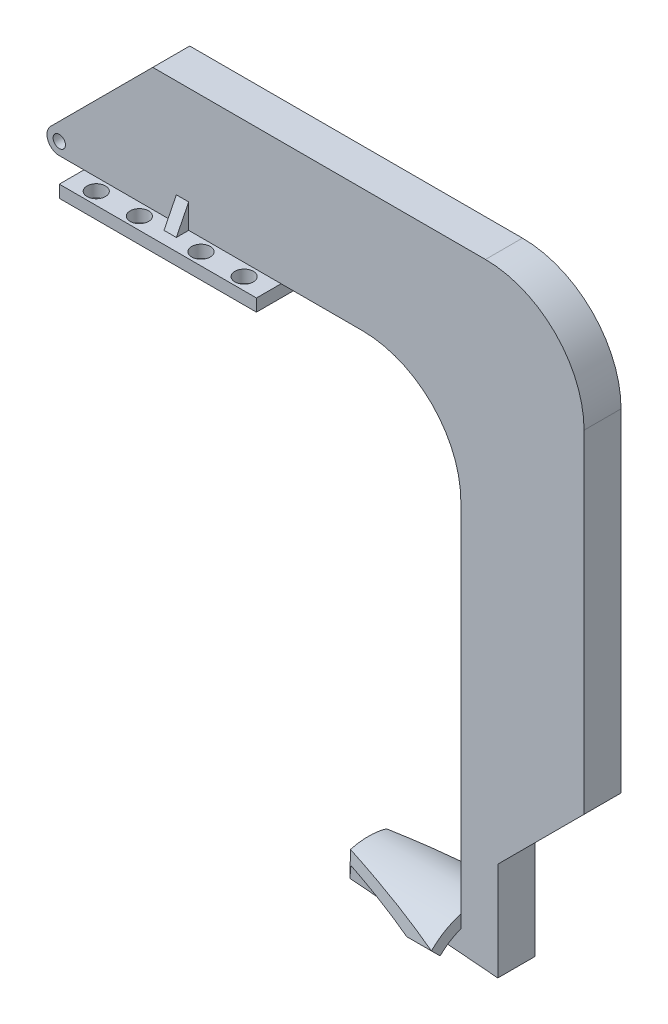
SolidWorks part; units mm, degrees
material "Stainless Steel (ferritic)"
ref_plane "Front Plane" through (0, 0, 0) normal (0, 0, 1) x (1, 0, 0)
ref_plane "Top Plane" through (0, 0, 0) normal (0, 1, 0) x (1, 0, 0)
ref_plane "Right Plane" through (0, 0, 0) normal (1, 0, 0) x (0, 0, -1)
sketch "Sketch1" plane through (0, 0, 0) normal (0, 0, 1) x (1, 0, 0)
  line L0 (-7.0711, 7.0711) -> (75.8579, 90)
  line L1 (75.8579, 90) -> (345.8579, 90)
  line L2 (425.8579, 10) -> (425.8579, -260)
  line L3 (425.8579, -260) -> (355.8579, -330)
  line L4 (355.8579, -330) -> (355.8579, -410)
  line L5 (355.8579, -410) -> (235.8579, -400)
  line L6 (235.8579, -400) -> (235.8579, -380)
  line L7 (235.8579, -380) -> (325.8579, -380)
  line L8 (325.8579, -380) -> (325.8579, -90)
  line L9 (245.8579, -10) -> (0, -10)
  arc A0 (325.8579, -90) -> (245.8579, -10) centre (245.8579, -90) ccw
  arc A1 (345.8579, 90) -> (425.8579, 10) centre (345.8579, 10) cw
  arc A2 (-7.0711, 7.0711) -> (0, -10) centre (0, 0) ccw
  circle A3 centre (0, 0) radius 5
  point P24 (325.8579, -10)
  point P27 (425.8579, 90)
  dimension "D11" = 80
  dimension "D12" = 20
  dimension "D13" = 10
  dimension "D1" = 500
  dimension "D2" = 100
  dimension "D3" = 100
  dimension "D4" = 30
  dimension "D5" = 45
  dimension "D6" = 350
  dimension "D7" = 370
  dimension "D8" = 10
  dimension "D9" = 350
  dimension "D10" = 120
extrude "Boss-Extrude1" add sketch "Sketch1" along normal blind 30
sketch "Sketch2" plane through (0, -10, 0) normal (0, -1, 0) x (1, 0, 0)
  line L0 (0, 30) -> (0, 0) construction
  line L1 (20, -20) -> (180, -20)
  line L2 (20, -20) -> (20, 50)
  line L3 (20, 50) -> (180, 50)
  line L4 (180, -20) -> (180, 50)
  line L5 (0, 30) -> (0, 0)
  point P6 (0, 15)
  point P7 (20, 15)
  line M3 (0, 0) -> (245.8579, 0)
  line M5 (245.8579, 30) -> (0, 30)
  dimension "D1" = 160
  dimension "D2" = 70
  dimension "D3" = 20
extrude "Boss-Extrude2" add sketch "Sketch2" along normal blind 10 contours L4 L3 L2 M5 | L4 L2 M3 M5 | L1 L4 L2 M3
ref_plane "Plane2" through (100, 0, 0) normal (-1, 0, 0) x (0, 0, 1)
sketch "Sketch5" plane through (100, 0, 0) normal (-1, 0, 0) x (0, 0, 1)
  line L0 (30, 10) -> (40, -10)
  line L1 (30, -10) -> (30, 7.0711) construction
  line L2 (30, -10) -> (50, -10) construction
  line L3 (30, 90) -> (30, 7.0711) construction
  point P6 (30, 10.9704)
  point P9 (0, 0)
  point P10 (42.7835, -10)
  dimension "D1" = 10
  dimension "D2" = 20
rib "Rib1" sketch "Sketch5" sketch "Sketch5" thickness 10 extrusion direction parallel to sketch draft on no parameters "D1"=10
sketch "Sketch7" plane through (100, 0, 0) normal (-1, 0, 0) x (0, 0, 1)
  line L0 (0, 10) -> (-10, -10)
  line L1 (0, 90) -> (0, 7.0711) construction
  line L2 (-20, -10) -> (0, -10) construction
  dimension "D1" = 20
  dimension "D2" = 10
rib "Rib17" sketch "Sketch7" sketch "Sketch7" thickness 10 extrusion direction parallel to sketch draft on no parameters "D1"=10
sketch "Sketch8" plane through (0, -20, 0) normal (0, -1, 0) x (1, 0, 0)
  line L0 (20, 0) -> (95, 0) construction
  line L1 (105, 0) -> (180, 0) construction
  line L2 (105, 30) -> (180, 30) construction
  line L3 (20, 30) -> (95, 30) construction
  line L4 (20, 0) -> (95, 0)
  line L5 (105, 0) -> (180, 0)
  line L6 (105, 30) -> (180, 30)
  line L7 (20, 30) -> (95, 30)
  line L8 (180, 0) -> (180, 30) construction
  line L9 (180, 0) -> (180, 30)
  line L10 (40, 40) -> (40, -10) construction
  line L11 (20, 50) -> (20, 30) construction
  line L12 (40, 40) -> (75, 40) construction
  line L13 (125, 40) -> (160, 40) construction
  circle A0 centre (40, 40) radius 7.5
  circle A1 centre (75, 40) radius 7.5
  circle A2 centre (125, 40) radius 7.5
  circle A3 centre (160, 40) radius 7.5
  circle A4 centre (40, -10) radius 7.5
  circle A5 centre (75, -10) radius 7.5
  circle A6 centre (125, -10) radius 7.5
  circle A7 centre (160, -10) radius 7.5
  point P24 (180, 15)
  point P25 (40, 15)
  point P26 (57.5, 40)
  point P27 (20, 40)
  point P28 (57.5, 30)
  point P29 (142.5, 40)
  point P30 (142.5, 30)
  dimension "D1" = 15
  dimension "D2" = 35
  dimension "D3" = 35
extrude "Cut-Extrude1" cut sketch "Sketch8" against normal blind 10 contours A0 | A1 | A4 | A5 | A6 | A7 | A3 | A2
sketch "Sketch9" plane through (325.8579, 0, 0) normal (-1, 0, 0) x (0, 0, 1)
  line L0 (-23.8909, -394.0242) -> (-16.8198, -401.0952)
  line L1 (46.8198, -401.0952) -> (53.8909, -394.0242)
  line L2 (15, -432.915) -> (15, -424.2734) construction
  line L3 (53.8909, -394.0242) -> (15, -432.915) construction
  line L4 (15, -432.915) -> (-23.8909, -394.0242) construction
  arc A0 (53.8909, -394.0242) -> (-23.8909, -394.0242) centre (15, -432.915) ccw
  arc A1 (46.8198, -401.0952) -> (-16.8198, -401.0952) centre (15, -432.915) ccw
  circle A2 centre (15, -432.915) radius 55 construction
  circle A3 centre (15, -432.915) radius 45 construction
  dimension "D1" = 110
  dimension "D3" = 90
  dimension "D2" = 10
extrude "Boss-Extrude3" add sketch "Sketch9" along normal up to surface (90 mm away) up to face at (235.8579, -390, 15)
sketch "Sketch10" plane through (-31.4768, -377.7221, 0) normal (-0.083, -0.9965, 0) x (0.9965, -0.083, 0)
  line L4 (357.4542, 53.8909) -> (268.2613, 30)
  line L5 (357.4542, -23.8909) -> (268.2613, 0)
  line L9 (374.5465, 58.4692) -> (256.226, 26.7763)
  line L10 (256.226, 26.7763) -> (256.226, 62.0562)
  line L11 (256.226, 62.0562) -> (374.5465, 58.4692)
  line L15 (268.2613, 30) -> (388.6773, 30) construction
  line L16 (374.0822, -28.3448) -> (258.0752, 2.7284)
  line L17 (258.0752, 2.7284) -> (258.0752, -32.7213)
  line L18 (258.0752, -32.7213) -> (374.0822, -28.3448)
  line L19 (268.2613, 0) -> (388.6773, 0) construction
  ellipse E0 centre (360.6839, 15) end of major axis (360.6839, 70) minor radius 4.5675 (356.2896, 0) -> (357.4542, -23.8909) ccw construction
  ellipse E1 centre (360.6839, 15) end of major axis (360.6839, 70) minor radius 4.5675 (357.4542, 53.8909) -> (356.2896, 30) ccw construction
  ellipse E2 centre (360.6839, 15) end of major axis (360.6839, 70) minor radius 4.5675 (356.2896, 0) -> (357.4542, -23.8909) ccw
  ellipse E3 centre (360.6839, 15) end of major axis (360.6839, 70) minor radius 4.5675 (357.4542, 53.8909) -> (356.2896, 30) ccw
  point P31 (254.5938, -32.7213)
  point P37 (254.9431, -32.7213)
  point P38 (258.0752, -32.7213)
  dimension "D1" = 32.7213
  dimension "D2" = 116.007
  dimension "D3" = 35.2799
  dimension "D4" = 118.3205
  dimension "D5" = 32.0562
  dimension "D6" = 10.1861
extrude "Cut-Extrude3" cut sketch "Sketch10" against normal blind 30 contours L9 L10 L11 | L18 L16 L17
